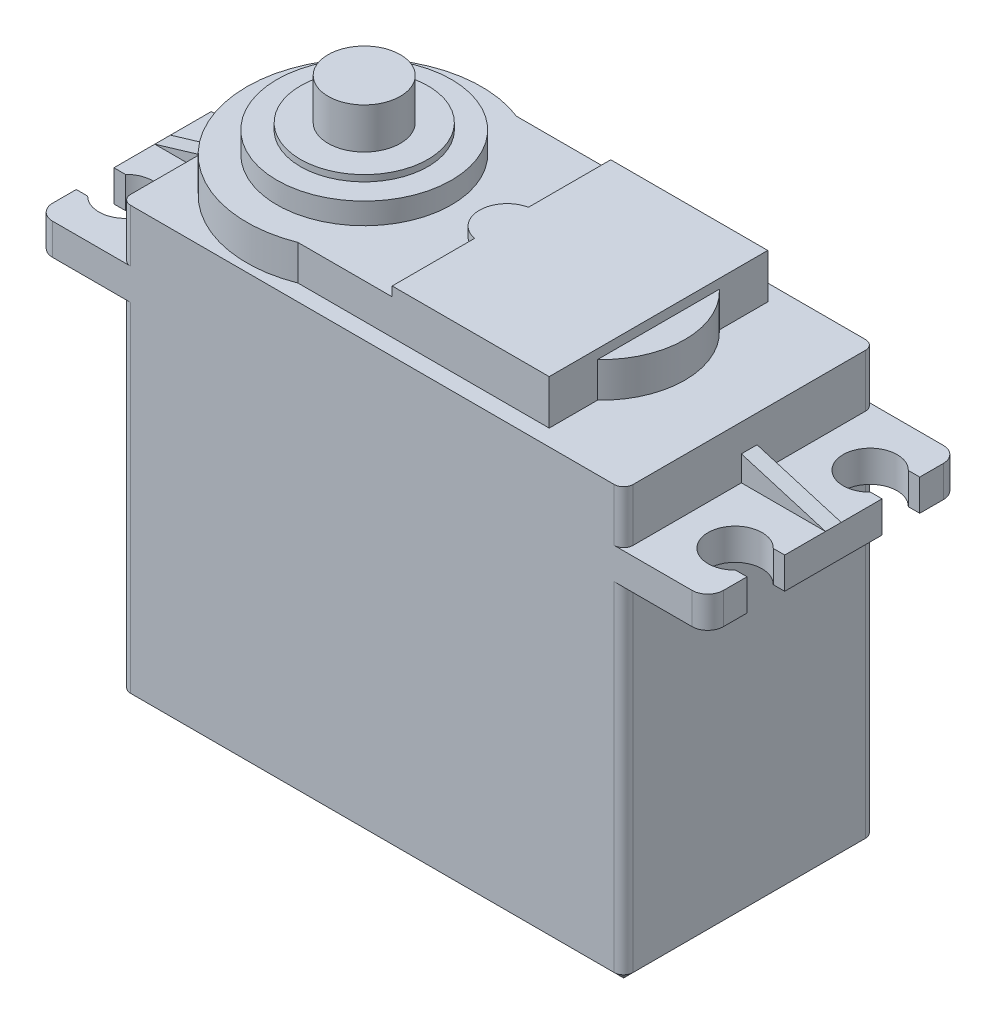
SolidWorks part; units mm, degrees
ref_plane "Front Plane" through (0, 0, 0) normal (0, 0, 1) x (1, 0, 0)
ref_plane "Top Plane" through (0, 0, 0) normal (0, 1, 0) x (1, 0, 0)
ref_plane "Right Plane" through (0, 0, 0) normal (1, 0, 0) x (0, 0, -1)
sketch "Sketch1" plane through (0, 0, 0) normal (0, 1, 0) x (1, 0, 0)
  line L1 (0, 0) -> (40, 0)
  line L2 (0, 0) -> (0, -20)
  line L3 (0, -20) -> (40, -20)
  line L4 (40, 0) -> (40, -20)
  dimension "D1" = 20
  dimension "D2" = 40
extrude "Boss-Extrude1" add sketch "Sketch1" along normal blind 34.4
sketch "Sketch3" plane through (0, 34.4, 0) normal (0, 1, 0) x (1, 0, 0)
  line L0 (12.7753, -1.3) -> (32.7753, -1.3)
  line L1 (32.7753, -1.3) -> (32.7753, -5.15)
  line L2 (32.7753, -18.7) -> (12.7753, -18.7)
  line L3 (0, -10) -> (40, -10) construction
  line L4 (32.7753, -14.85) -> (32.7753, -18.7)
  line L5 (0, 0) -> (0, -20) construction
  line L6 (40, -20) -> (40, 0) construction
  line L7 (12.7753, -1.3) -> (12.7753, -18.7) construction
  line L8 (32.7753, -5.15) -> (32.7753, -14.85) construction
  arc A0 (12.7753, -18.7) -> (12.7753, -1.3) centre (9.35, -10) cw
  arc A1 (32.7753, -5.15) -> (32.7753, -14.85) centre (28.2247, -10) cw
  dimension "D1" = 9.35
  dimension "D5" = 20
  dimension "D2" = 17.4
  dimension "D3" = 9.7
  dimension "D4" = 2.1
extrude "Boss-Extrude2" add sketch "Sketch3" along normal blind 2.8
sketch "Sketch4" plane through (0, 37.2, 0) normal (0, 1, 0) x (1, 0, 0)
  circle A0 centre (9.35, -10) radius 6.95
  arc A1 (12.7753, -1.3) -> (12.7753, -18.7) centre (9.35, -10) ccw construction
  dimension "D1" = 13.9
extrude "Boss-Extrude3" add sketch "Sketch4" along normal blind 1.7
sketch "Sketch5" plane through (0, 38.9, 0) normal (0, 1, 0) x (1, 0, 0)
  circle A0 centre (9.35, -10) radius 5.075
  circle A1 centre (9.35, -10) radius 6.95 construction
  dimension "D1" = 10.15
extrude "Boss-Extrude4" add sketch "Sketch5" along normal blind 0.5
sketch "Sketch6" plane through (0, 39.4, 0) normal (0, 1, 0) x (1, 0, 0)
  circle A0 centre (9.35, -10) radius 2.875
  circle A1 centre (9.35, -10) radius 5.075 construction
  dimension "D1" = 5.75
extrude "Boss-Extrude5" add sketch "Sketch6" along normal blind 3.25
sketch "Sketch7" plane through (0, 37.2, 0) normal (0, 1, 0) x (1, 0, 0)
  line L0 (32.7753, -1.3) -> (32.7753, -18.7)
  line L1 (32.7753, -18.7) -> (20.2753, -18.7)
  line L2 (20.2753, -18.7) -> (20.2753, -12.15)
  line L3 (20.721, -10) -> (32.7753, -10) construction
  line L4 (20.2753, -7.85) -> (20.2753, -1.3)
  line L5 (20.2753, -1.3) -> (32.7753, -1.3)
  line L6 (20.2753, -12.15) -> (20.2753, -7.85) construction
  arc A0 (20.2753, -12.15) -> (20.2753, -7.85) centre (20.721, -10) cw
  dimension "D1" = 12.5
  dimension "D3" = 1.75
  dimension "D2" = 4.3
extrude "Boss-Extrude6" add sketch "Sketch7" along normal blind 0.75
sketch "Sketch8" plane through (40, 0, 0) normal (1, 0, 0) x (0, 0, -1)
  line L0 (-20, 34.4) -> (-20, 0) construction
  line L1 (-20, 30.2) -> (0, 30.2)
  line L2 (-20, 30.2) -> (-20, 27.7)
  line L3 (-20, 27.7) -> (0, 27.7)
  line L4 (0, 30.2) -> (0, 27.7)
  line L5 (0, 34.4) -> (0, 0) construction
  line L6 (-20, 34.4) -> (0, 34.4) construction
  dimension "D1" = 2.5
  dimension "D2" = 6.7
extrude "Boss-Extrude7" add sketch "Sketch8" along normal blind 6.7
sketch "Sketch9" plane through (0, 0, 0) normal (-1, 0, 0) x (0, 0, 1)
  line L0 (20, 34.4) -> (20, 0) construction
  line L1 (0, 30.2) -> (20, 30.2)
  line L2 (0, 30.2) -> (0, 27.7)
  line L3 (0, 27.7) -> (20, 27.7)
  line L4 (20, 30.2) -> (20, 27.7)
  line L5 (0, 34.4) -> (0, 0) construction
  line L6 (0, 34.4) -> (10, 34.4) construction
  dimension "D1" = 2.5
  dimension "D2" = 6.7
extrude "Boss-Extrude8" add sketch "Sketch9" along normal blind 6.7
sketch "Sketch10" plane through (0, 30.2, 0) normal (0, 1, 0) x (1, 0, 0)
  line L0 (-4.25, -4.625) -> (-4.25, -15.375) construction
  line L1 (44.25, -4.625) -> (44.25, -15.375) construction
  line L2 (46.7, -10) -> (44.25, -10) construction
  line L3 (46.7, 0) -> (46.7, -20) construction
  line L4 (40, 0) -> (40, -20) construction
  line L5 (45.7903, -3.125) -> (46.7, -3.125)
  line L6 (46.7, -3.125) -> (46.7, -6.125)
  line L7 (46.7, -6.125) -> (45.7903, -6.125)
  line L8 (45.7903, -13.875) -> (46.7, -13.875)
  line L9 (46.7, -13.875) -> (46.7, -16.875)
  line L10 (46.7, -16.875) -> (45.7903, -16.875)
  line L11 (-4.25, -10) -> (-6.7, -10) construction
  line L12 (-6.7, -20) -> (-6.7, 0) construction
  line L13 (0, -20) -> (0, 0) construction
  line L14 (-5.7903, -3.125) -> (-6.7, -3.125)
  line L15 (-6.7, -3.125) -> (-6.7, -6.125)
  line L16 (-6.7, -6.125) -> (-5.7903, -6.125)
  line L17 (-5.7903, -13.875) -> (-6.7, -13.875)
  line L18 (-6.7, -13.875) -> (-6.7, -16.875)
  line L19 (-6.7, -16.875) -> (-5.7903, -16.875)
  arc A0 (-5.7903, -3.125) -> (-5.7903, -6.125) centre (-4.25, -4.625) cw
  arc A1 (-5.7903, -16.875) -> (-5.7903, -13.875) centre (-4.25, -15.375) ccw
  arc A2 (45.7903, -13.875) -> (45.7903, -16.875) centre (44.25, -15.375) ccw
  arc A4 (45.7903, -6.125) -> (45.7903, -3.125) centre (44.25, -4.625) cw
  dimension "D1" = 4.25
  dimension "D3" = 2.15
  dimension "D4" = 3
  dimension "D5" = 4.25
  dimension "D2" = 10.75
extrude "Cut-Extrude1" cut sketch "Sketch10" against normal through all
sketch "Sketch11" plane through (0, 0, 0) normal (-1, 0, 0) x (0, 0, 1)
  line L1 (6.925, 3.85) -> (13.075, 3.85)
  line L2 (6.925, 3.85) -> (6.925, 0)
  line L3 (6.925, 0) -> (13.075, 0)
  line L4 (13.075, 3.85) -> (13.075, 0)
  line L5 (0, 0) -> (20, 0) construction
  line L7 (0, 0) -> (6.925, 0) construction
  line L8 (13.075, 0) -> (20, 0) construction
  dimension "D1" = 6.15
  dimension "D2" = 3.85
extrude "Boss-Extrude9" add sketch "Sketch11" along normal blind 1
fillet "Fillet1" radius 0.75 8 edges at (0, 13.85, 0) (0, 32.3, 0) (40, 13.85, 0) (40, 32.3, 0) (40, 13.85, 20) (40, 32.3, 20) (0, 13.85, 20) (0, 32.3, 20)
fillet "Fillet2" radius 1.25 4 edges at (46.7, 28.95, 20) (-6.7, 28.95, 20) (-6.7, 28.95, 0) (46.7, 28.95, 0)
chamfer "Chamfer1" distance 0.75 angle 45 9 edges at (20, 0, 0) (0, 0, 3.8375) (0, 0, 16.1625) (40, 0, 10) (0.2197, 0, 0.2197) (39.7803, 0, 0.2197) (0.2197, 0, 19.7803) (39.7803, 0, 19.7803) (20, 0, 20)
ref_plane "Plane1" through (0, 0, 10) normal (0, 0, -1) x (-1, 0, 0)
ref_plane "Plane2" through (20, 0, 0) normal (1, 0, 0) x (0, 0, -1)
sketch "Sketch12" plane through (0, 0, 10) normal (0, 0, -1) x (-1, 0, 0)
  line L0 (-40, 32.2) -> (-46.7, 30.2)
  line L1 (-46.7, 30.2) -> (-40, 30.2)
  line L2 (-40, 30.2) -> (-40, 32.2)
  line L3 (6.7, 30.2) -> (0, 32.2)
  line L4 (0, 32.2) -> (0, 30.2)
  line L5 (0, 30.2) -> (6.7, 30.2)
  dimension "D1" = 2
  dimension "D2" = 2
extrude "Boss-Extrude10" add sketch "Sketch12" along normal blind 0.625 and the other way blind 0.625
